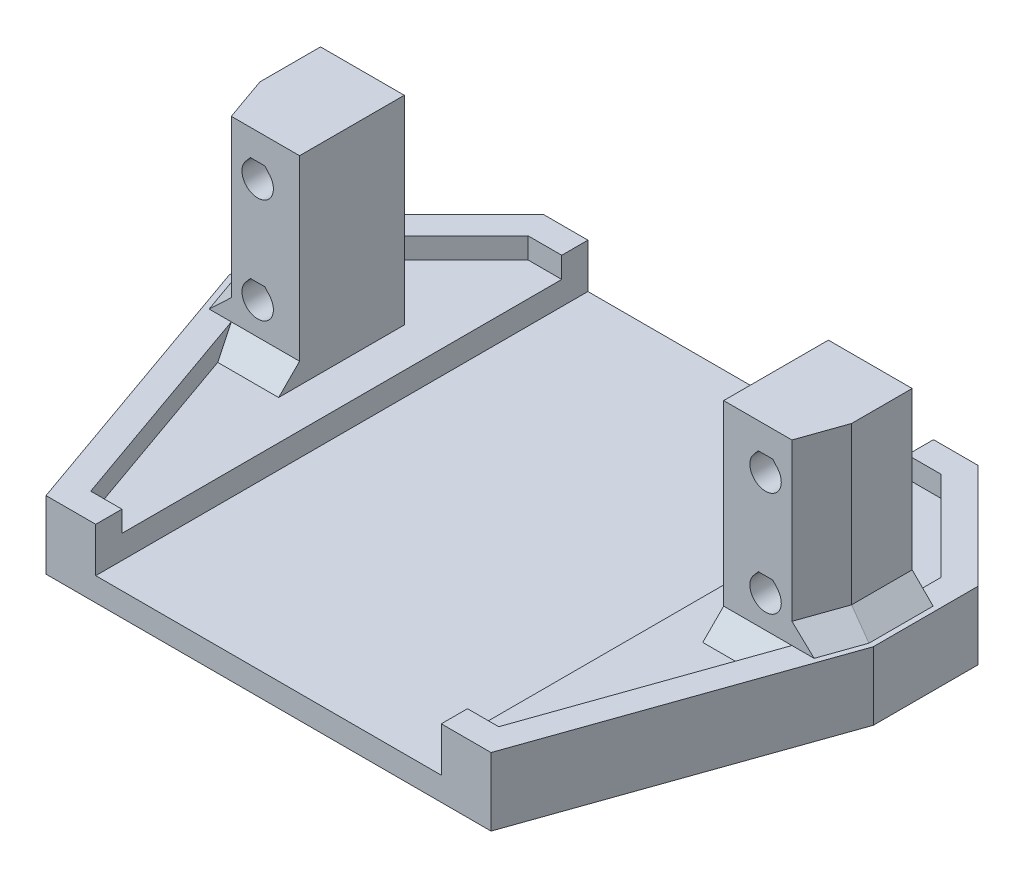
SolidWorks part; units mm, degrees
ref_plane "Front Plane" through (0, 0, 0) normal (0, 0, 1) x (1, 0, 0)
ref_plane "Top Plane" through (0, 0, 0) normal (0, 1, 0) x (1, 0, 0)
ref_plane "Right Plane" through (0, 0, 0) normal (1, 0, 0) x (0, 0, -1)
sketch "Sketch1" plane through (0, 0, 0) normal (0, 1, 0) x (1, 0, 0)
  line L0 (0, 0) -> (0, 47) construction
  line L1 (21.25, 0) -> (-21.25, 0)
  line L2 (-30.75, 27) -> (-30.75, 37)
  line L3 (-30.75, 37) -> (-20.75, 47)
  line L4 (-20.75, 47) -> (20.75, 47)
  line L5 (-30.75, 27) -> (-21.25, 0)
  line L6 (30.75, 27) -> (21.25, 0)
  line L7 (30.75, 37) -> (20.75, 47)
  line L8 (30.75, 27) -> (30.75, 37)
  dimension "D1" = 10
  dimension "D2" = 47
  dimension "D3" = 45
  dimension "D4" = 30.75
  dimension "D5" = 10
  dimension "D6" = 42.5
extrude "Boss-Extrude1" add sketch "Sketch1" against normal blind 4.5
sketch "Sketch2" plane through (0, 0, 0) normal (0, 1, 0) x (1, 0, 0)
  line L0 (0, 47) -> (0, 0) construction
  line L1 (20.75, 47) -> (-20.75, 47) construction
  line L2 (-16.5, 47) -> (-16.5, 0)
  line L3 (-21.25, 0) -> (21.25, 0) construction
  line L4 (16.5, 47) -> (16.5, 0)
  line L5 (-16.5, 47) -> (16.5, 47)
  line L6 (-16.5, 0) -> (16.5, 0)
  dimension "D1" = 16.5
extrude "Cut-Extrude1" cut sketch "Sketch2" against normal blind 2.25
sketch "Sketch3" plane through (0, 0, 0) normal (0, 1, 0) x (1, 0, 0)
  line L0 (-21.25, 0) -> (-16.5, 0) construction
  line L1 (-30.75, 27) -> (-21.25, 0) construction
  line L2 (-30.75, 37) -> (-30.75, 27) construction
  line L3 (-20.75, 47) -> (-30.75, 37) construction
  line L4 (-16.5, 47) -> (-20.75, 47) construction
  line L5 (16.5, 0) -> (21.25, 0) construction
  line L6 (21.25, 0) -> (30.75, 27) construction
  line L7 (30.75, 27) -> (30.75, 37) construction
  line L8 (30.75, 37) -> (20.75, 47) construction
  line L9 (20.75, 47) -> (16.5, 47) construction
  line L10 (-21.25, 0) -> (-16.5, 0)
  line L11 (-30.75, 27) -> (-21.25, 0)
  line L12 (-30.75, 37) -> (-30.75, 27)
  line L13 (-20.75, 47) -> (-30.75, 37)
  line L14 (-16.5, 47) -> (-20.75, 47)
  line L15 (16.5, 0) -> (21.25, 0)
  line L16 (21.25, 0) -> (30.75, 27)
  line L17 (30.75, 27) -> (30.75, 37)
  line L18 (30.75, 37) -> (20.75, 47)
  line L19 (20.75, 47) -> (16.5, 47)
  line L20 (-16.5, 44.5) -> (-19.7145, 44.5)
  line L21 (-19.7145, 44.5) -> (-28.25, 35.9645)
  line L22 (-28.25, 35.9645) -> (-28.25, 27.427)
  line L23 (-28.25, 27.427) -> (-19.4794, 2.5)
  line L24 (-19.4794, 2.5) -> (-16.5, 2.5)
  line L25 (16.5, 2.5) -> (19.4794, 2.5)
  line L26 (19.4794, 2.5) -> (28.25, 27.427)
  line L27 (28.25, 27.427) -> (28.25, 35.9645)
  line L28 (28.25, 35.9645) -> (19.7145, 44.5)
  line L29 (19.7145, 44.5) -> (16.5, 44.5)
  line L30 (-16.5, 2.5) -> (-16.5, 0)
  line L31 (-16.5, 44.5) -> (-16.5, 47)
  line L32 (16.5, 47) -> (16.5, 44.5)
  line L33 (16.5, 2.5) -> (16.5, 0)
  dimension "D1" = 2.5
extrude "Boss-Extrude2" add sketch "Sketch3" along normal blind 2
sketch "Sketch4" plane through (0, 0, 0) normal (0, 1, 0) x (1, 0, 0)
  line L0 (-20.25, 33.2145) -> (-20.25, 23.2145)
  line L1 (20.25, 23.2145) -> (20.25, 33.2145)
  line L2 (-20.25, 33.2145) -> (-28.25, 33.2145)
  line L3 (-28.25, 27.427) -> (-28.25, 35.9645) construction
  line L4 (-20.25, 23.2145) -> (-26.7678, 23.2145)
  line L5 (20.25, 33.2145) -> (28.25, 33.2145)
  line L6 (28.25, 35.9645) -> (28.25, 27.427) construction
  line L7 (20.25, 23.2145) -> (26.7678, 23.2145)
  line L8 (0, 47) -> (0, 0) construction
  line L9 (16.5, 47) -> (-16.5, 47) construction
  line L10 (-19.4794, 2.5) -> (-28.25, 27.427) construction
  line L11 (28.25, 27.427) -> (19.4794, 2.5) construction
  line L12 (-26.7678, 23.2145) -> (-28.25, 27.427)
  line L13 (-28.25, 27.427) -> (-28.25, 33.2145)
  line L14 (28.25, 33.2145) -> (28.25, 27.427)
  line L15 (28.25, 27.427) -> (26.7678, 23.2145)
  dimension "D1" = 20.25
  dimension "D2" = 2.75
  dimension "D3" = 10
extrude "Boss-Extrude3" add sketch "Sketch4" along normal blind 19
chamfer "Chamfer1" distance 2 angle 45 4 edges at (-28.25, 2, -30.3207) (-27.5089, 2, -25.3207) (27.5089, 2, -25.3207) (28.25, 2, -30.3207)
chamfer "Chamfer2" distance 2 angle 45 2 edges at (23.5089, 0, -23.2145) (-23.5089, 0, -23.2145)
sketch "Sketch5" plane through (0, 0, -23.2145) normal (0, 0, 1) x (1, 0, 0)
  line L0 (0, 0) -> (0, 24.1346) construction
  line L1 (-28.25, 10) -> (-20.25, 10) construction
  line L2 (-28.25, 19) -> (-28.25, 4) construction
  line L3 (-20.25, 19) -> (-20.25, 2) construction
  line L4 (-24.25, 10) -> (-24.25, 15) construction
  line L5 (-24.25, 10) -> (-24.25, 5) construction
  line L6 (-26.7678, 19) -> (-20.25, 19) construction
  line L7 (-26.2081, 15) -> (-22.2919, 15) construction
  line L8 (-22.2919, 15) -> (-23.5505, 16.5) construction
  line L9 (-23.5505, 16.5) -> (-24.9495, 16.5) construction
  line L10 (-24.9495, 16.5) -> (-26.2081, 15) construction
  line L11 (-26.2081, 5) -> (-22.2919, 5) construction
  line L12 (-22.2919, 5) -> (-23.5505, 6.5) construction
  line L13 (-23.5505, 6.5) -> (-24.9495, 6.5) construction
  line L14 (-24.9495, 6.5) -> (-26.2081, 5) construction
  line L15 (-24.9495, 16.5) -> (-25.3991, 15.9642)
  line L16 (-23.1009, 15.9642) -> (-23.5505, 16.5)
  line L17 (-23.5505, 16.5) -> (-24.9495, 16.5)
  line L18 (-23.1009, 5.9642) -> (-23.5505, 6.5)
  line L19 (-23.5505, 6.5) -> (-24.9495, 6.5)
  line L20 (-24.9495, 6.5) -> (-25.3991, 5.9642)
  line L21 (23.1009, 5.9642) -> (23.5505, 6.5)
  line L22 (24.9495, 6.5) -> (25.3991, 5.9642)
  line L23 (23.5505, 6.5) -> (24.9495, 6.5)
  line L24 (24.9495, 16.5) -> (25.3991, 15.9642)
  line L25 (23.5505, 16.5) -> (24.9495, 16.5)
  line L26 (23.1009, 15.9642) -> (23.5505, 16.5)
  arc A0 (-25.3991, 15.9642) -> (-23.1009, 15.9642) centre (-24.25, 15) ccw
  arc A1 (-25.3991, 5.9642) -> (-23.1009, 5.9642) centre (-24.25, 5) ccw
  arc A2 (25.3991, 5.9642) -> (23.1009, 5.9642) centre (24.25, 5) cw
  arc A3 (25.3991, 15.9642) -> (23.1009, 15.9642) centre (24.25, 15) cw
  dimension "D3" = 3
  dimension "D1" = 4
  dimension "D2" = 10
  dimension "D4" = 50
  dimension "D5" = 50
extrude "Cut-Extrude2" cut sketch "Sketch5" against normal up to next
